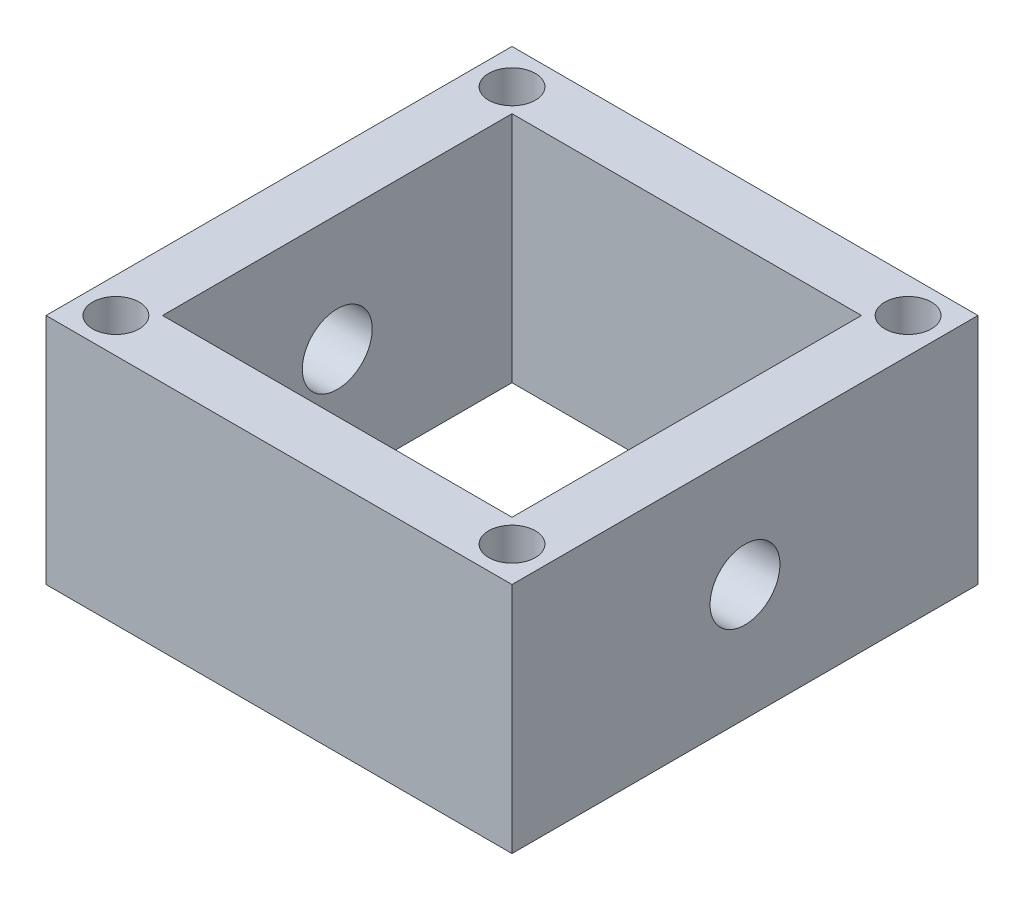
SolidWorks part; units mm, degrees
material "1060 Alloy"
ref_plane "Front Plane" through (0, 0, 0) normal (0, 0, 1) x (1, 0, 0)
ref_plane "Top Plane" through (0, 0, 0) normal (0, 1, 0) x (1, 0, 0)
ref_plane "Right Plane" through (0, 0, 0) normal (1, 0, 0) x (0, 0, -1)
sketch "Sketch1" plane through (0, 0, 0) normal (0, 1, 0) x (1, 0, 0)
  line L1 (-7.5, 7.5) -> (7.5, 7.5)
  line L2 (-7.5, 7.5) -> (-7.5, -7.5)
  line L3 (-7.5, -7.5) -> (7.5, -7.5)
  line L4 (7.5, 7.5) -> (7.5, -7.5)
  line L5 (-7.5, 7.5) -> (7.5, -7.5) construction
  line L6 (-7.5, -7.5) -> (7.5, 7.5) construction
  line L7 (-10, 10) -> (10, 10)
  line L8 (-10, 10) -> (-10, -10)
  line L9 (-10, -10) -> (10, -10)
  line L10 (10, 10) -> (10, -10)
  line L11 (-10, 10) -> (10, -10) construction
  line L12 (-10, -10) -> (10, 10) construction
  point P0 (0, 0)
  point P6 (0, 0)
  dimension "D1" = 15
  dimension "D2" = 15
  dimension "D3" = 20
  dimension "D4" = 20
extrude "Boss-Extrude1" add sketch "Sketch1" along normal blind 10
sketch "Sketch2" plane through (-10, 0, 0) normal (-1, 0, 0) x (0, 0, 1)
  line L0 (-10, 5) -> (10, 5) construction
  line L2 (-10, 10) -> (-10, 0) construction
  line L3 (10, 10) -> (10, 0) construction
  circle A0 centre (0, 5) radius 1.5
  dimension "D1" = 3
extrude "Cut-Extrude1" cut sketch "Sketch2" against normal through all
sketch "Sketch3" plane through (0, 10, 0) normal (0, 1, 0) x (1, 0, 0)
  line L0 (10, 10) -> (-10, 10) construction
  line L1 (-10, 10) -> (-10, -10) construction
  line L2 (10, -10) -> (10, 10) construction
  line L3 (-10, -10) -> (10, -10) construction
  circle A0 centre (-8.5, 8.5) radius 1
  circle A1 centre (8.5, 8.5) radius 1
  circle A2 centre (8.5, -8.5) radius 1
  circle A3 centre (-8.5, -8.5) radius 1
  dimension "D3" = 2
  dimension "D5" = 2
  dimension "D6" = 2
  dimension "D7" = 2
  dimension "D1" = 1.5
  dimension "D2" = 1.5
  dimension "D4" = 1.5
  dimension "D8" = 1.5
extrude "Cut-Extrude2" cut sketch "Sketch3" against normal blind 6
